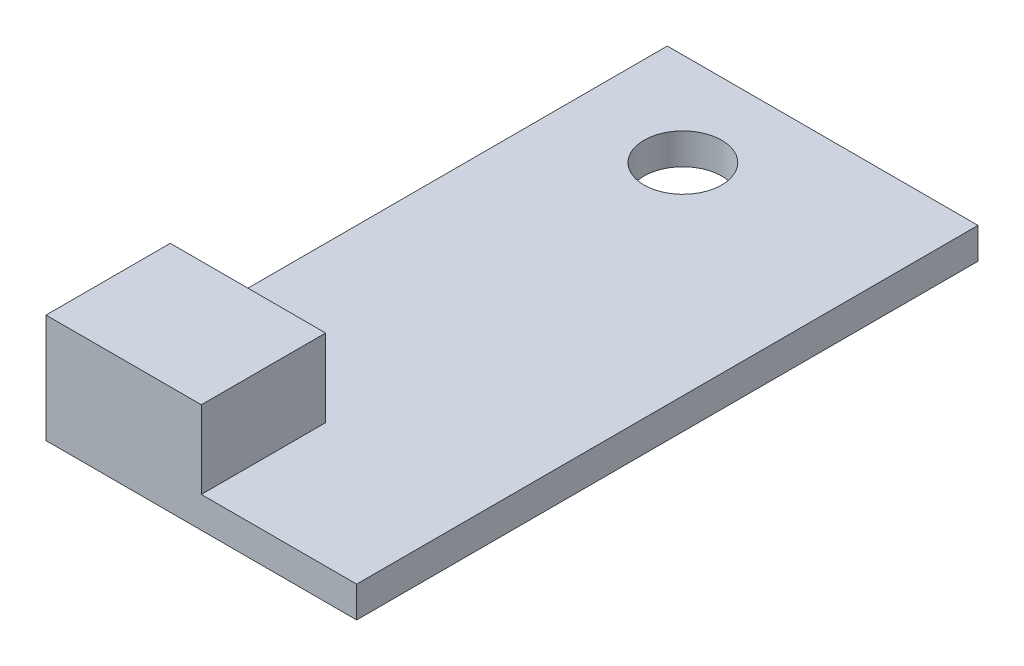
SolidWorks part; units mm, degrees
ref_plane "Front Plane" through (0, 0, 0) normal (0, 0, 1) x (1, 0, 0)
ref_plane "Top Plane" through (0, 0, 0) normal (0, 1, 0) x (1, 0, 0)
ref_plane "Right Plane" through (0, 0, 0) normal (1, 0, 0) x (0, 0, -1)
sketch "Sketch1" plane through (0, 0, 0) normal (0, 1, 0) x (1, 0, 0)
  line L5 (0, 0) -> (100, 0)
  line L6 (0, 0) -> (0, 200)
  line L7 (0, 200) -> (100, 200)
  line L8 (100, 0) -> (100, 200)
  dimension "D1" = 200
  dimension "D2" = 100
extrude "Boss-Extrude1" add sketch "Sketch1" along normal blind 10 contours L8 L7 L6 L5
sketch "Sketch2" plane through (0, 10, 0) normal (0, 1, 0) x (1, 0, 0)
  line L1 (0, 0) -> (50, 0)
  line L2 (0, 0) -> (0, 40)
  line L3 (0, 40) -> (50, 40)
  line L4 (50, 0) -> (50, 40)
  dimension "D1" = 50
  dimension "D2" = 40
extrude "Boss-Extrude2" add sketch "Sketch2" along normal blind 25 contours L2 L1 L4 L3
hole_wizard "Ø25.0 (25) Diameter Hole1" positions "Sketch3" profile "Sketch4" hole size "Ø25.0" standard "ANSI Metric" end condition through all
sketch "Sketch3" plane through (0, 10, 0) normal (0, 1, 0) x (1, 0, 0)
  line L0 (0, 200) -> (100, 200) construction
  line L1 (100, 0) -> (100, 200) construction
  point P0 (35, 170)
  point P8 (35, 170)
  dimension "D1" = 30
  dimension "D2" = 65
sketch "Sketch4" plane through (35, 10, -170) normal (1, 0, 0) x (0, 0, 1)
  line L0 (0, 0) -> (0, 10)
  line L1 (0, 10) -> (12.5, 10)
  line L2 (12.5, 10) -> (12.5, 0)
  line L5 (12.5, 0) -> (0, 0)
  line L11 (0, -6.35) -> (0, 107.95) construction
  dimension "Thru Hole Dia." = 25
  dimension "Thru Hole Depth" = 10
